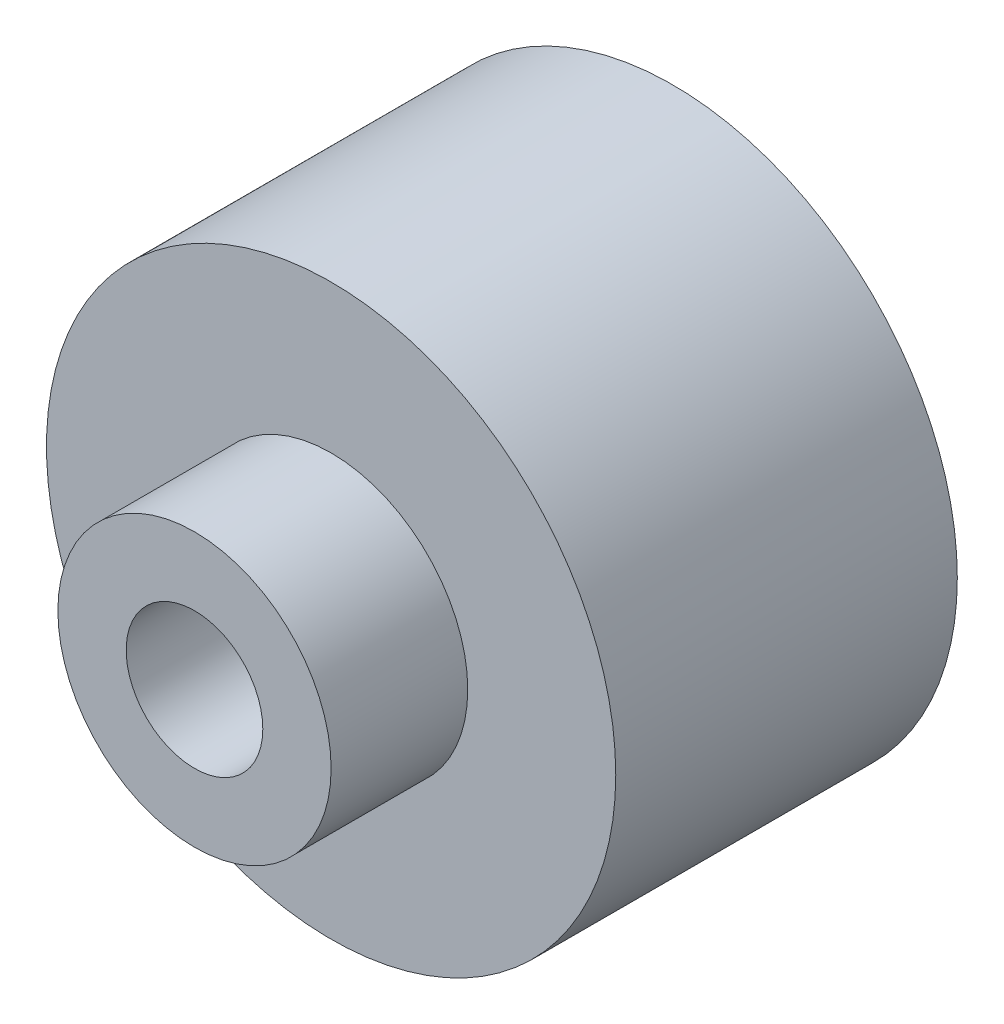
SolidWorks part; units mm, degrees
material "Настроенная пользователем пластмасса"
ref_plane "Спереди" through (0, 0, 0) normal (0, 0, 1) x (1, 0, 0)
ref_plane "Сверху" through (0, 0, 0) normal (0, 1, 0) x (1, 0, 0)
ref_plane "Справа" through (0, 0, 0) normal (1, 0, 0) x (0, 0, -1)
sketch "Эскиз1" plane through (0, 0, 0) normal (0, 1, 0) x (1, 0, 0)
  line L0 (3, 0) -> (3, -21)
  line L1 (3, -21) -> (6, -21)
  line L2 (6, -21) -> (6, -15)
  line L3 (6, -15) -> (12.5, -15)
  line L4 (12.5, -15) -> (12.5, 0)
  line L5 (12.5, 0) -> (3, 0)
  line L6 (0, 0) -> (0, -21) construction
revolve "Повернуть1" add sketch "Эскиз1" angle 360 about L6
